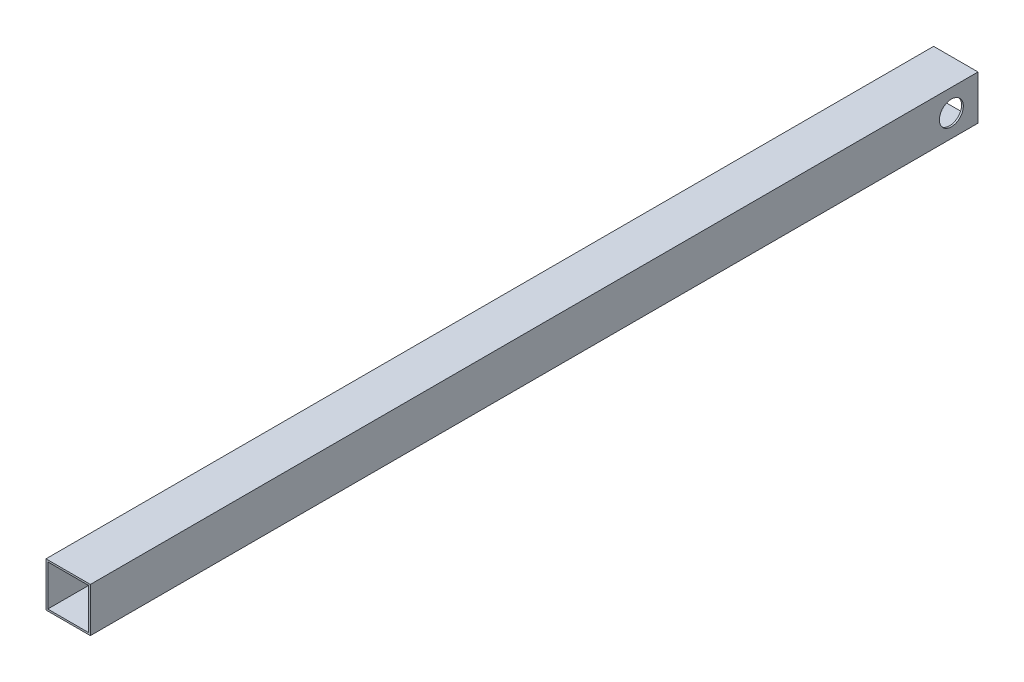
SolidWorks part; units mm, degrees
ref_plane "Front Plane" through (0, 0, 0) normal (0, 0, 1) x (1, 0, 0)
ref_plane "Top Plane" through (0, 0, 0) normal (0, 1, 0) x (1, 0, 0)
ref_plane "Right Plane" through (0, 0, 0) normal (1, 0, 0) x (0, 0, -1)
sketch "Sketch1" plane through (0, 0, 0) normal (0, 0, 1) x (1, 0, 0)
  line L1 (-12.5, 12.5) -> (12.5, 12.5)
  line L2 (-12.5, 12.5) -> (-12.5, -12.5)
  line L3 (-12.5, -12.5) -> (12.5, -12.5)
  line L4 (12.5, 12.5) -> (12.5, -12.5)
  line L5 (-12.5, 12.5) -> (12.5, -12.5) construction
  line L6 (-12.5, -12.5) -> (12.5, 12.5) construction
  point P0 (0, 0)
  dimension "D1" = 25
  dimension "D2" = 25
extrude "Boss-Extrude1" add sketch "Sketch1" along normal blind 500
sketch "Sketch2" plane through (0, 0, 500) normal (0, 0, 1) x (1, 0, 0)
  line L0 (-12.5, 12.5) -> (-12.5, -12.5) construction
  line L1 (-11.5, 11.5) -> (11.5, 11.5)
  line L2 (-11.5, 11.5) -> (-11.5, -11.5)
  line L3 (-11.5, -11.5) -> (11.5, -11.5)
  line L4 (11.5, 11.5) -> (11.5, -11.5)
  line L5 (-11.5, 11.5) -> (11.5, -11.5) construction
  line L6 (-11.5, -11.5) -> (11.5, 11.5) construction
  line L8 (-12.5, -12.5) -> (12.5, -12.5) construction
  point P0 (0, 0)
  dimension "D1" = 1
  dimension "D2" = 1
extrude "Cut-Extrude1" cut sketch "Sketch2" against normal through all
sketch "Sketch3" plane through (12.5, 0, 0) normal (1, 0, 0) x (0, 0, -1)
  line L0 (0, -12.5) -> (0, 12.5) construction
  circle A0 centre (-15, 0) radius 6.75
  dimension "D1" = 15
  dimension "13.5" = 13.5
extrude "Cut-Extrude2" cut sketch "Sketch3" against normal through all
